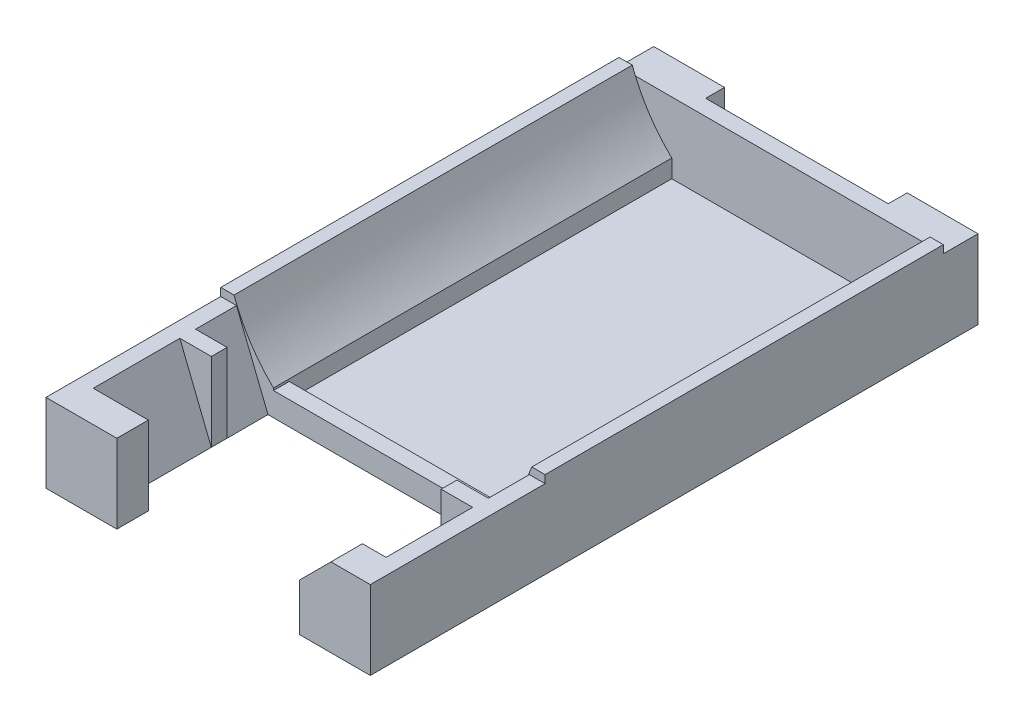
SolidWorks part; units mm, degrees
ref_plane "Front Plane" through (0, 0, 0) normal (0, 0, 1) x (1, 0, 0)
ref_plane "Top Plane" through (0, 0, 0) normal (0, 1, 0) x (1, 0, 0)
ref_plane "Right Plane" through (0, 0, 0) normal (1, 0, 0) x (0, 0, -1)
sketch "Sketch1" plane through (0, 0, 0) normal (0, 0, 1) x (1, 0, 0)
  line L0 (0, 0) -> (0, 8.6) construction
  line L1 (-10.3, -8.6) -> (10.3, -8.6)
  line L2 (-10.3, -8.6) -> (-10.3, 8.6)
  line L3 (-10.3, 8.6) -> (10.3, 8.6)
  line L4 (10.3, -8.6) -> (10.3, 8.6)
  line L5 (-10.3, -8.6) -> (10.3, 8.6) construction
  line L6 (-10.3, 8.6) -> (10.3, -8.6) construction
  line L7 (0, 2.3) -> (0, -2) construction
  line L8 (3.1, 2.3) -> (3.1, -2)
  line L9 (-3.1, 2.3) -> (-3.1, -2)
  arc A0 (3.1, 2.3) -> (-3.1, 2.3) centre (0, 2.3) ccw
  arc A1 (-3.1, -2) -> (3.1, -2) centre (0, -2) ccw
  point P0 (0, 0)
  point P10 (0, 0.15)
  dimension "D1" = 20.6
  dimension "D2" = 17.2
  dimension "D3" = 3.2
  dimension "D4" = 6.2
  dimension "D5" = 3.5
extrude "Boss-Extrude1" add sketch "Sketch1" along normal blind 2.5
sketch "Sketch2" plane through (0, 0, 0) normal (0, 0, -1) x (-1, 0, 0)
  line L0 (10.3, 8.6) -> (10.3, -8.6) construction
  line L1 (-10.3, -8.6) -> (10.3, -8.6)
  line L2 (-10.3, -8.6) -> (-10.3, -7.1)
  line L3 (-10.3, -7.1) -> (10.3, -7.1)
  line L4 (10.3, -8.6) -> (10.3, -7.1)
  dimension "D1" = 1.5
extrude "Boss-Extrude2" add sketch "Sketch2" along normal blind 25.3
sketch "Sketch3" plane through (0, 0, -25.3) normal (0, 0, -1) x (-1, 0, 0)
  line L0 (10.3, 8.6) -> (10.3, -7.1) construction
  line L1 (-10.3, -8.6) -> (10.3, -8.6)
  line L2 (-10.3, -8.6) -> (-10.3, -3.6)
  line L3 (-10.3, -3.6) -> (10.3, -3.6)
  line L4 (10.3, -8.6) -> (10.3, -3.6)
  dimension "D1" = 5
extrude "Boss-Extrude3" add sketch "Sketch3" along normal blind 1
sketch "Sketch4" plane through (0, -7.1, 0) normal (0, 1, 0) x (1, 0, 0)
  line L0 (0, 25.3) -> (0, 0) construction
  line L1 (-10.3, 25.3) -> (10.3, 25.3) construction
  line L3 (-6.95, 0) -> (6.95, 0)
  line L4 (-6.95, 0) -> (-6.95, 25.3)
  line L5 (-6.95, 25.3) -> (6.95, 25.3)
  line L6 (6.95, 0) -> (6.95, 25.3)
  line L7 (-6.95, 0) -> (6.95, 25.3) construction
  line L8 (-6.95, 25.3) -> (6.95, 0) construction
  line L9 (-10.3, 0) -> (10.3, 0)
  line L10 (-10.3, 0) -> (-10.3, 25.3)
  line L11 (-10.3, 25.3) -> (10.3, 25.3)
  line L12 (10.3, 0) -> (10.3, 25.3)
  line L13 (-10.3, 0) -> (10.3, 25.3) construction
  line L14 (-10.3, 25.3) -> (10.3, 0) construction
  point P5 (0, 12.65)
  point P10 (0, 12.65)
  line M9 (-10.3, 0) -> (10.3, 0)
  line M10 (10.3, 0) -> (10.3, 25.3)
  line M11 (10.3, 25.3) -> (-10.3, 25.3)
  line M12 (-10.3, 25.3) -> (-10.3, 0)
  dimension "D1" = 13.9
extrude "Boss-Extrude4" add sketch "Sketch4" along normal blind 4 contours L4 M9 M11 M12 | L6 M9 M10 M11
sketch "Sketch5" plane through (0, 0, 0) normal (0, 0, -1) x (-1, 0, 0)
  line L0 (6.95, -7.1) -> (-6.95, -7.1) construction
  line L1 (6.95, -7.1) -> (-6.95, -7.1)
  circle A0 centre (0, 0.3) radius 10.05
  point P5 (0, 0.7056)
  line M2 (-6.95, -3.1) -> (-6.95, -7.1)
  line M4 (6.95, -7.1) -> (6.95, -3.1)
  line M5 (6.95, -3.1) -> (10.3, -3.1)
  line M7 (10.3, 8.6) -> (-10.3, 8.6)
  line M9 (-10.3, -3.1) -> (-6.95, -3.1)
  line M10 (-3.1, -2) -> (-3.1, 2.3)
  arc M11 (-3.1, 2.3) -> (3.1, 2.3) centre (0, 2.3) cw
  line M12 (3.1, 2.3) -> (3.1, -2)
  arc M13 (3.1, -2) -> (-3.1, -2) centre (0, -2) cw
  dimension "D1" = 20.1
  dimension "D2" = 0.3
extrude "Cut-Extrude2" cut sketch "Sketch5" along normal up to surface (25.3 mm away) contours A0 L1 M7 M9 M2 M4 M5 M13 M10 M11 M12 | A0 M4 M5 | A0 M9 M2 up to face at (0, -5.35, -25.3)
chamfer "Chamfer1" distance 2 angle 45 2 edges at (-10.3, 8.6, 1.25) (10.3, 8.6, 1.25)
sketch "Sketch6" plane through (0, 0, -26.3) normal (0, 0, -1) x (-1, 0, 0)
  line L0 (-7.3, -8.6) -> (-10.3, -8.6)
  line L1 (-10.3, -8.6) -> (10.3, -8.6) construction
  line L2 (-10.3, -8.6) -> (-10.3, -3.6)
  line L3 (-10.3, -3.6) -> (-9.3, -3.6)
  line L4 (10.3, -3.6) -> (-10.3, -3.6) construction
  line L5 (-9.3, -3.6) -> (-7.3, -8.6)
  line L6 (0, -8.6) -> (0, 0) construction
  line L7 (9.3, -3.6) -> (7.3, -8.6)
  line L8 (10.3, -3.6) -> (9.3, -3.6)
  line L9 (10.3, -8.6) -> (10.3, -3.6)
  line L10 (7.3, -8.6) -> (10.3, -8.6)
  dimension "D1" = 3
  dimension "D2" = 1
extrude "Boss-Extrude5" add sketch "Sketch6" along normal blind 1.2
sketch "Sketch7" plane through (0, 0, -27.5) normal (0, 0, -1) x (-1, 0, 0)
  line L0 (0, -8.6) -> (0, 0) construction
  line L1 (-10.3, -8.6) -> (-5.8, -8.6)
  line L2 (-10.3, -8.6) -> (-10.3, -3.6)
  line L3 (-10.3, -3.6) -> (-5.8, -3.6)
  line L4 (-5.8, -8.6) -> (-5.8, -3.6)
  line L5 (-7.3, -8.6) -> (7.3, -8.6) construction
  line L6 (5.8, -8.6) -> (5.8, -3.6)
  line L7 (10.3, -3.6) -> (5.8, -3.6)
  line L8 (10.3, -8.6) -> (10.3, -3.6)
  line L9 (10.3, -8.6) -> (5.8, -8.6)
  dimension "D1" = 4.5
extrude "Boss-Extrude6" add sketch "Sketch7" against normal blind 1.5
sketch "Sketch8" plane through (0, 0, 2.5) normal (0, 0, 1) x (1, 0, 0)
  circle A0 centre (0, 0) radius 16.7932
extrude "Cut-Extrude3" cut sketch "Sketch8" against normal up to surface (2.5 mm away) up to face at (0, -0.8675, 0)
sketch "Sketch9" plane through (0, 0, 0) normal (0, 0, 1) x (1, 0, 0)
  line L4 (7.3, -8.6) -> (10.3, -8.6)
  line L5 (10.3, -8.6) -> (10.3, -3.6)
  line L6 (10.3, -3.6) -> (9.3, -3.6)
  line L7 (9.3, -3.6) -> (7.3, -8.6)
  line L8 (7.3, -8.6) -> (10.3, -8.6)
  line L9 (10.3, -8.6) -> (10.3, -3.6)
  line L10 (10.3, -3.6) -> (9.3, -3.6)
  line L11 (9.3, -3.6) -> (7.3, -8.6)
  line L12 (-10.3, -8.6) -> (-7.3, -8.6)
  line L13 (-7.3, -8.6) -> (-9.3, -3.6)
  line L14 (-9.3, -3.6) -> (-10.3, -3.6)
  line L15 (-10.3, -3.6) -> (-10.3, -8.6)
  line L16 (-10.3, -8.6) -> (-7.3, -8.6)
  line L17 (-7.3, -8.6) -> (-9.3, -3.6)
  line L18 (-9.3, -3.6) -> (-10.3, -3.6)
  line L19 (-10.3, -3.6) -> (-10.3, -8.6)
  dimension "D1" = 0
  dimension "D2" = 0
extrude "Boss-Extrude7" add sketch "Sketch9" along normal blind 11.1
ref_plane "Plane1" through (0, 0, 2.6) normal (0, 0, 1) x (1, 0, 0)
sketch "Sketch10" plane through (0, 0, 2.6) normal (0, 0, 1) x (1, 0, 0)
  line L0 (-9.3, -3.6) -> (-7.3, -3.6)
  line L1 (-9.2624, -3.6) -> (9.2624, -3.6) construction
  line L2 (-7.3, -3.6) -> (-7.3, -8.6)
  line L3 (9.3, -3.6) -> (7.3, -3.6)
  line L4 (-10.3, -8.6) -> (-7.3, -8.6)
  line L5 (-7.3, -8.6) -> (-9.3, -3.6)
  line L6 (-9.3, -3.6) -> (-10.3, -3.6)
  line L7 (-10.3, -3.6) -> (-10.3, -8.6)
  line L8 (-10.3, -8.6) -> (-7.3, -8.6)
  line L9 (-7.3, -8.6) -> (-9.3, -3.6) construction
  line L10 (-9.3, -3.6) -> (-10.3, -3.6)
  line L11 (-10.3, -3.6) -> (-10.3, -8.6)
  line L12 (7.3, -8.6) -> (10.3, -8.6)
  line L13 (10.3, -8.6) -> (10.3, -3.6)
  line L14 (10.3, -3.6) -> (9.3, -3.6)
  line L15 (9.3, -3.6) -> (7.3, -8.6)
  line L16 (7.3, -8.6) -> (10.3, -8.6)
  line L17 (10.3, -8.6) -> (10.3, -3.6)
  line L18 (10.3, -3.6) -> (9.3, -3.6)
  line L19 (9.3, -3.6) -> (7.3, -8.6) construction
  line L20 (7.3, -3.6) -> (7.3, -8.6)
  dimension "D1" = 0
  dimension "D2" = 0
extrude "Boss-Extrude8" add sketch "Sketch10" along normal blind 1
sketch "Sketch11" plane through (0, 0, 11.1) normal (0, 0, 1) x (1, 0, 0)
  line L4 (-5.8, -8.6) -> (-5.8, -3.6)
  line L5 (-5.8, -3.6) -> (-10.3, -3.6)
  line L6 (-10.3, -3.6) -> (-10.3, -8.6)
  line L7 (-10.3, -8.6) -> (-5.8, -8.6)
  line L8 (-5.8, -8.6) -> (-5.8, -3.6)
  line L9 (-5.8, -3.6) -> (-10.3, -3.6)
  line L10 (-10.3, -3.6) -> (-10.3, -8.6)
  line L11 (-10.3, -8.6) -> (-5.8, -8.6)
  line L12 (5.8, -8.6) -> (10.3, -8.6)
  line L13 (5.8, -3.6) -> (5.8, -8.6)
  line L14 (10.3, -3.6) -> (5.8, -3.6)
  line L15 (10.3, -8.6) -> (10.3, -3.6)
  line L16 (5.8, -8.6) -> (10.3, -8.6)
  line L17 (5.8, -3.6) -> (5.8, -8.6)
  line L18 (10.3, -3.6) -> (5.8, -3.6)
  line L19 (10.3, -8.6) -> (10.3, -3.6)
  dimension "D1" = 0
  dimension "D2" = 0
extrude "Boss-Extrude9" add sketch "Sketch11" against normal blind 2
chamfer "Chamfer2" distance 2 angle 45 1 edges at (5.8, -3.6, 10.1)
sketch "Sketch12" plane through (0, -7.1, 0) normal (0, 1, 0) x (1, 0, 0)
  line L0 (6.95, 0) -> (6.95, 25.3) construction
  line L1 (-6.95, 25.3) -> (6.95, 25.3)
  line L2 (-6.95, 25.3) -> (-6.95, 1)
  line L3 (-6.95, 1) -> (6.95, 1)
  line L4 (6.95, 25.3) -> (6.95, 1)
  line L5 (-6.95, 0) -> (6.95, 0) construction
  dimension "D1" = 1
extrude "Cut-Extrude4" cut sketch "Sketch12" against normal blind 1
